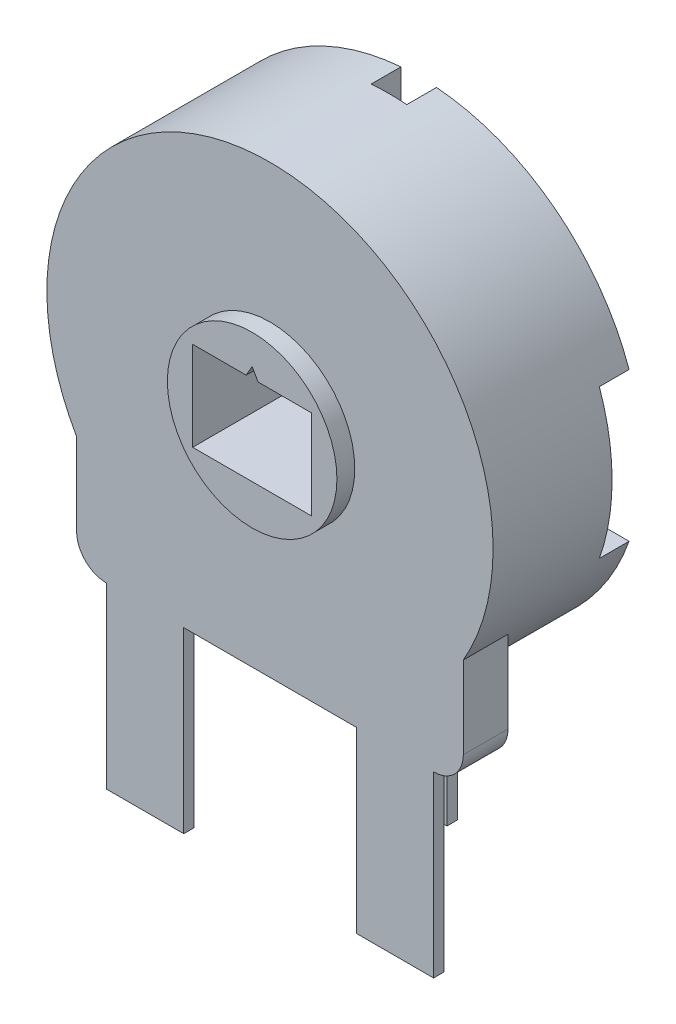
SolidWorks part; units mm, degrees
material "POM Acetal Copolymer"
ref_plane "Front Plane" through (0, 0, 0) normal (0, 0, 1) x (1, 0, 0)
ref_plane "Top Plane" through (0, 0, 0) normal (0, 1, 0) x (1, 0, 0)
ref_plane "Right Plane" through (0, 0, 0) normal (1, 0, 0) x (0, 0, -1)
sketch "Sketch2" plane through (0, 0, 0) normal (0, 0, 1) x (1, 0, 0)
  circle A0 centre (0, 0) radius 7.5
  dimension "D1" = 15
extrude "Boss-Extrude1" add sketch "Sketch2" along normal blind 5
sketch "Sketch3" plane through (0, 0, 0) normal (0, 0, -1) x (-1, 0, 0)
  line L1 (-2, -1.5) -> (2, -1.5)
  line L2 (-2, -1.5) -> (-2, 1.5)
  line L3 (-2, 1.5) -> (2, 1.5)
  line L4 (2, -1.5) -> (2, 1.5)
  line L5 (-2, -1.5) -> (2, 1.5) construction
  line L6 (-2, 1.5) -> (2, -1.5) construction
  line L7 (0, 1.8494) -> (-0.3026, 1.3253)
  line L8 (-0.3026, 1.3253) -> (0.3026, 1.3253)
  line L9 (0.3026, 1.3253) -> (0, 1.8494)
  circle A0 centre (0, 1.5) radius 0.1747 construction
  point P0 (0, 0)
  dimension "D1" = 3
  dimension "D2" = 4
extrude "Cut-Extrude1" cut sketch "Sketch3" against normal through all contours L9 L8 L7 L3 L2 L1 L4
sketch "Sketch4" plane through (0, 0, 0) normal (0, 0, -1) x (-1, 0, 0)
  line L0 (8.4184, -2.5) -> (4.5816, 2.5) construction
  line L1 (-4.5816, -2.5) -> (-8.4184, -2.5)
  line L2 (-4.5816, -2.5) -> (-4.5816, 2.5)
  line L3 (-4.5816, 2.5) -> (-8.4184, 2.5)
  line L4 (-8.4184, -2.5) -> (-8.4184, 2.5)
  line L5 (-4.5816, -2.5) -> (-8.4184, 2.5) construction
  line L6 (-4.5816, 2.5) -> (-8.4184, -2.5) construction
  line L7 (4.5816, -2.5) -> (4.5816, 2.5)
  line L8 (8.4184, -2.5) -> (8.4184, 2.5)
  line L9 (8.4184, -2.5) -> (4.5816, -2.5)
  line L10 (8.4184, 2.5) -> (4.5816, 2.5)
  line L11 (8.4184, 2.5) -> (4.5816, -2.5) construction
  line L13 (-0.5984, 4.9795) -> (0.5984, 4.9795)
  line L14 (-0.5984, 4.9795) -> (-0.5984, 8.0205)
  line L15 (-0.5984, 8.0205) -> (0.5984, 8.0205)
  line L16 (0.5984, 4.9795) -> (0.5984, 8.0205)
  line L17 (-0.5984, 4.9795) -> (0.5984, 8.0205) construction
  line L18 (-0.5984, 8.0205) -> (0.5984, 4.9795) construction
  line L19 (-0.5984, -7.916) -> (0.5984, -7.916)
  line L20 (-0.5984, -7.916) -> (-0.5984, -5.084)
  line L21 (-0.5984, -5.084) -> (0.5984, -5.084)
  line L22 (0.5984, -7.916) -> (0.5984, -5.084)
  line L23 (-0.5984, -7.916) -> (0.5984, -5.084) construction
  line L24 (-0.5984, -5.084) -> (0.5984, -7.916) construction
  circle A1 centre (0, 0) radius 3.85
  circle A2 centre (0, 0) radius 6.5
  circle A3 centre (0, 0) radius 6.5
  circle A4 centre (0, 0) radius 7.5 construction
  circle A5 centre (0, 0) radius 7.5
  point P1 (-6.5, 0)
  point P9 (6.5, 0)
  point P16 (0, 6.5)
  point P21 (0, -6.5)
  circle M2 centre (0, 0) radius 7.5
  dimension "D2" = 7.7
  dimension "D3" = 5
  dimension "D1" = 1
extrude "Cut-Extrude2" cut sketch "Sketch4" against normal blind 1 contours A3 L3 L1 M2 | L3 A3 L1 L2 | L10 A3 L16 L13 L14 L3 L2 L1 L20 L21 L22 L9 L7 A1 | L16 A3 L14 L13 | A3 L16 L14 M2 | L9 A3 L10 L7 | A3 L9 L10 M2 | L20 A3 L22 L21 | A3 L20 L22 M2
sketch "Sketch7" plane through (0, 0, 5) normal (0, 0, 1) x (1, 0, 0)
  circle A0 centre (0, 0) radius 2.85
  circle A1 centre (0, 0) radius 7.5
  circle A2 centre (0, 0) radius 7.5
  line M3 (-2, -1.5) -> (-2, 1.5)
  line M4 (-2, 1.5) -> (-0.2017, 1.5)
  line M5 (-0.2017, 1.5) -> (0, 1.8494)
  line M6 (0, 1.8494) -> (0.2017, 1.5)
  line M7 (0.2017, 1.5) -> (2, 1.5)
  line M8 (2, 1.5) -> (2, -1.5)
  line M9 (2, -1.5) -> (-2, -1.5)
  dimension "D2" = 5.7
  dimension "D1" = 0
extrude "Boss-Extrude2" add sketch "Sketch7" along normal blind 0.6 contours A0 M9 M3 M4 M5 M6 M7 M8
sketch "Sketch8" plane through (0, 0, 5) normal (0, 0, 1) x (1, 0, 0)
  line L1 (-5.5, -7.5) -> (5.5, -7.5)
  line L2 (-6.5, -6.5) -> (-6.5, -2.85)
  line L3 (-6.5, -2.85) -> (6.5, -2.85)
  line L4 (6.5, -6.5) -> (6.5, -2.85)
  circle A0 centre (0, 0) radius 7.5 construction
  circle A1 centre (0, 0) radius 2.85 construction
  circle A2 centre (0, 0) radius 2.85 construction
  arc A3 (6.5, -6.5) -> (5.5, -7.5) centre (5.5, -6.5) cw
  arc A4 (-6.5, -6.5) -> (-5.5, -7.5) centre (-5.5, -6.5) ccw
  point P6 (0, -2.85)
  point P13 (6.5, -7.5)
  point P16 (-6.5, -7.5)
  dimension "D1" = 1
  dimension "D2" = 13
extrude "Boss-Extrude3" add sketch "Sketch8" against normal blind 1.5
sketch "Sketch9" plane through (0, -7.5, 0) normal (0, -1, 0) x (1, 0, 0)
  line L0 (-1.3, 0) -> (1.3, 0)
  line L1 (-5.5, 5) -> (-2.9, 5)
  line L2 (-5.5, 5) -> (-5.5, 4.65)
  line L3 (-5.5, 4.65) -> (-2.9, 4.65)
  line L4 (-2.9, 5) -> (-2.9, 4.65)
  line L5 (5.5, 5) -> (2.9, 5)
  line L6 (5.5, 5) -> (5.5, 4.65)
  line L7 (5.5, 4.65) -> (2.9, 4.65)
  line L8 (2.9, 5) -> (2.9, 4.65)
  line L9 (-1.3, 0.35) -> (-1.3, 0)
  line L10 (-1.3, 0.35) -> (1.3, 0.35)
  line L11 (1.3, 0.35) -> (1.3, 0)
  line L13 (-7.0711, 0) -> (-0.5984, 0) construction
  dimension "D1" = 0.35
  dimension "D2" = 2.6
extrude "Boss-Extrude4" add sketch "Sketch9" along normal blind 6
